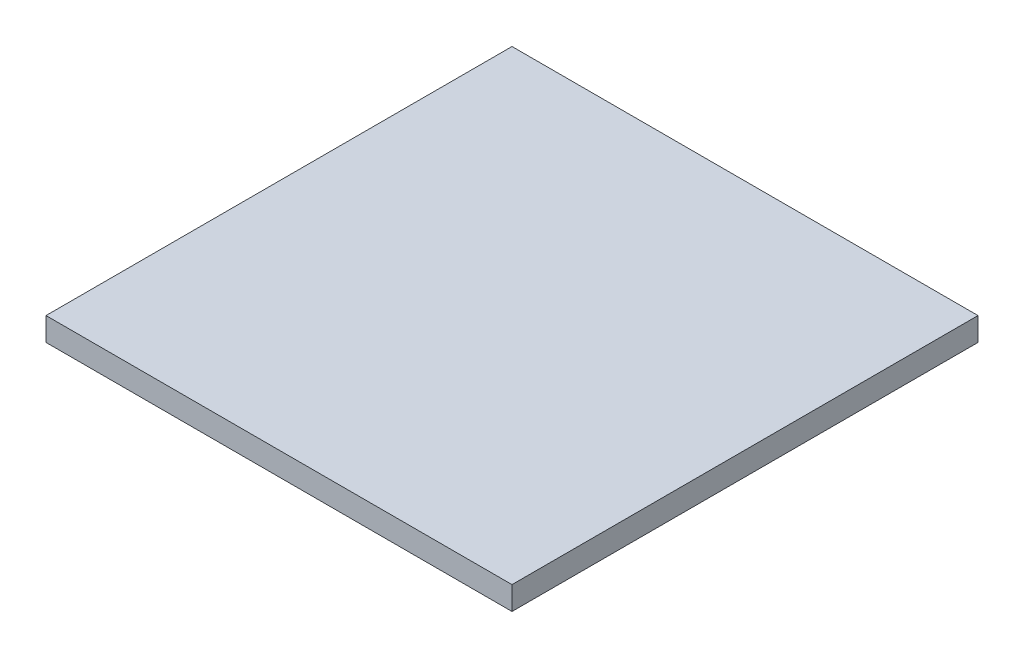
SolidWorks part; units mm, degrees
ref_plane "Alzado" through (0, 0, 0) normal (0, 0, 1) x (1, 0, 0)
ref_plane "Planta" through (0, 0, 0) normal (0, 1, 0) x (1, 0, 0)
ref_plane "Vista lateral" through (0, 0, 0) normal (1, 0, 0) x (0, 0, -1)
sketch "SkTablaMovilPlataforma" plane through (0, 0, 0) normal (0, 1, 0) x (1, 0, 0)
  line L1 (-250, -250) -> (250, -250)
  line L2 (-250, -250) -> (-250, 250)
  line L3 (-250, 250) -> (250, 250)
  line L4 (250, -250) -> (250, 250)
extrude "TablaMovilPlataforma" add sketch "SkTablaMovilPlataforma" along normal blind 25 flip side to cut separate body
